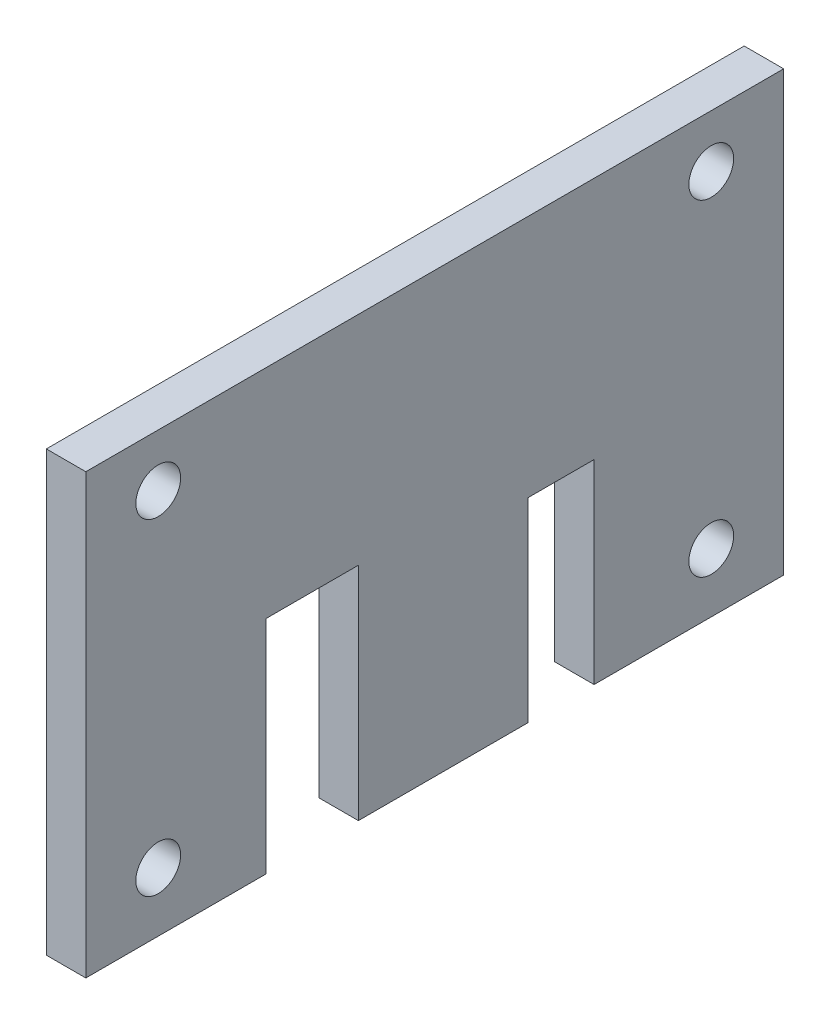
SolidWorks part; units mm, degrees
ref_plane "Front Plane" through (0, 0, 0) normal (0, 0, 1) x (1, 0, 0)
ref_plane "Top Plane" through (0, 0, 0) normal (0, 1, 0) x (1, 0, 0)
ref_plane "Right Plane" through (0, 0, 0) normal (1, 0, 0) x (0, 0, -1)
ref_plane "PX72_4" through (72.4, 0, 0) normal (1, 0, 0) x (0, 0, -1)
sketch "Sketch1" plane through (72.4, 0, 0) normal (1, 0, 0) x (0, 0, -1)
  line L0 (-99.5, -26.8) -> (-46.5, -26.8)
  line L1 (-46.5, -26.8) -> (-46.5, 6.5)
  line L2 (-46.5, 6.5) -> (-99.5, 6.5)
  line L3 (-99.5, 6.5) -> (-99.5, -26.8)
extrude "Cover Plate" add sketch "Sketch1" along normal blind 3
ref_plane "PX71_4" through (71.4, 0, 0) normal (1, 0, 0) x (0, 0, -1)
sketch "Sketch2" plane through (71.4, 0, 0) normal (1, 0, 0) x (0, 0, -1)
  line L0 (-85.8, -27.8) -> (-78.8, -27.8)
  line L1 (-78.8, -27.8) -> (-78.8, -10)
  line L2 (-78.8, -10) -> (-85.8, -10)
  line L3 (-85.8, -10) -> (-85.8, -27.8)
  line L4 (-65.9, -27.8) -> (-60.9, -27.8)
  line L5 (-60.9, -27.8) -> (-60.9, -12)
  line L6 (-60.9, -12) -> (-65.9, -12)
  line L7 (-65.9, -12) -> (-65.9, -27.8)
extrude "Cable Notches" cut sketch "Sketch2" along normal blind 5
sketch "Sketch3" plane through (71.4, 0, 0) normal (1, 0, 0) x (0, 0, -1)
  circle A0 centre (-94, -22.3) radius 1.7
  circle A1 centre (-94, 2.5) radius 1.7
  circle A2 centre (-52, -22.3) radius 1.7
  circle A3 centre (-52, 2.5) radius 1.7
extrude "Screw Holes" cut sketch "Sketch3" along normal blind 5
equation "\"BOARD_REAR\" = 86.0"
equation "\"BOARD_FRONT\" = 41.0"
equation "\"BOARD_END\" = 22.0"
equation "\"BOARD_ANGLED\" = 30.0"
equation "\"BOARD_DEPTH\" = 41.8431"
equation "\"PCB_T\" = 1.6"
equation "\"ABOVE_PCB\" = 14.0"
equation "\"BELOW_PCB\" = 6.0"
equation "\"MID_PARTS_H\" = 9.0"
equation "\"BOARD_HOLE_PILOT\" = 1.6"
equation "\"J2_X\" = 19.0"
equation "\"DUPONT_DROP\" = 14.0"
equation "\"BEND_R\" = 5.0"
equation "\"BOARD_GAP\" = 3.0"
equation "\"TOF_FOV\" = 25.0"
equation "\"TOF_MARGIN_DEG\" = 5.0"
equation "\"TOF_WIN_MARGIN\" = 1.0"
equation "\"TOF_Z\" = 9.0"
equation "\"TOF_SIDE_BEARING\" = 90.0"
equation "\"TOF_CONE_LEN\" = 70.0"
equation "\"CAM_W\" = 29.2"
equation "\"CAM_H\" = 28.2"
equation "\"CAM_D\" = 12.35"
equation "\"CAM_FRONT_Y\" = 43.0"
equation "\"CAM_BOTTOM_Z\" = 17.0"
equation "\"CAM_LENS_UP\" = 11.6"
equation "\"CAM_LENS_OPEN\" = 9.6"
equation "\"CAM_HFOV\" = 53.5"
equation "\"CAM_VFOV\" = 41.41"
equation "\"CAM_FOV_MARGIN\" = 3.0"
equation "\"CAM_FIT\" = 0.3"
equation "\"RIBBON_W\" = 16.0"
equation "\"RIBBON_T\" = 0.3"
equation "\"RIBBON_LEN\" = 150.0"
equation "\"RIBBON_EXIT_Y\" = 35.0"
equation "\"WALL\" = 2.4"
equation "\"HEAD_X\" = 48.4"
equation "\"HEAD_REAR_Y\" = -11.9"
equation "\"CAM_FOAM\" = 2.8"
equation "\"HEAD_FRONT_Y\" = 48.2"
equation "\"HEAD_TOP_Z\" = 50.6"
equation "\"HEAD_BOT_Z\" = -28.4"
equation "\"HEAD_SPLIT_Z\" = -4.0"
equation "\"SKIRT_T\" = 1.2"
equation "\"SKIRT_H\" = 3.0"
equation "\"SKIRT_FIT\" = 0.3"
equation "\"VISOR\" = 7.8"
equation "\"VISOR_Z\" = 40.0"
equation "\"ROOF_SLOPE_Y\" = 40.0"
equation "\"ROOF_CHAMFER\" = 10.0"
equation "\"REAR_CHAMFER\" = 10.0"
equation "\"CORNER_CHAMFER\" = 6.0"
equation "\"LOWER_SIDE_FACET\" = 6.0"
equation "\"LIGHTBAR_DEPTH\" = 1.0"
equation "\"HOOD_Z\" = 14.0"
equation "\"HOOD_L\" = 6.0"
equation "\"SIDE_HOOD_L\" = 4.0"
equation "\"INSERT_M3_D\" = 4.0"
equation "\"INSERT_M3_L\" = 6.0"
equation "\"M3_CLEAR\" = 3.4"
equation "\"M2_PILOT\" = 1.6"
equation "\"M25_PILOT\" = 2.2"
equation "\"BOX_X\" = 72.4"
equation "\"BOX_FRONT_Y\" = -11.9"
equation "\"BOX_REAR_Y\" = -124.4"
equation "\"BOX_BOT_Z\" = -28.4"
equation "\"BOX_TOP_Z\" = 26.0"
equation "\"LID_T\" = 2.4"
equation "\"LID_SKIRT\" = 1.6"
equation "\"LID_TONGUE_H\" = 3.0"
equation "\"LID_FIT\" = 0.3"
equation "\"PI_STANDOFF\" = 8.0"
equation "\"BOX_REAR_CHAMFER\" = 8.0"
equation "\"BOX_REAR_FACET\" = 4.0"
equation "\"VENT_UPSTAND\" = 3.0"
equation "\"TUBE_D\" = 22.2"
equation "\"TUBE_LINER\" = 1.0"
equation "\"MOUNT_Y\" = -70.0"
equation "\"RAIL_W\" = 30.0"
equation "\"RAIL_W2\" = 38.0"
equation "\"RAIL_H\" = 6.0"
equation "\"SLIDE\" = 0.3"
equation "\"STOP_T\" = 6.0"
equation "\"CLAMP_W\" = 40.0"
equation "\"CLAMP_HALF\" = 20.0"
equation "\"CLAMP_DROP\" = 12.0"
equation "\"CAP_T\" = 12.0"
equation "\"CLAMP_BOLT_OFF\" = 16.6"
equation "\"M5_INSERT_D\" = 6.4"
equation "\"M5_CLEAR\" = 5.5"
equation "\"LOCK_D\" = 3.3"
equation "\"POD_TILT_DEG\" = 0.0"
equation "\"PRINT_LIMIT\" = 180.0"
equation "\"PI5_L\" = 85.0"
equation "\"PI5_W\" = 56.0"
equation "\"PI5_T\" = 1.6"
equation "\"PI5_USBC_BX\" = 11.2"
equation "\"PI5_ETH_BY\" = 10.2"
equation "\"PI5_PORT_OVERHANG\" = 3.0"
equation "\"PI5_FPC_H\" = 5.0"
equation "\"PI5_FPC_USE\" = 0.0"
equation "\"PI5_PIN1_BX\" = 8.37"
equation "\"HEADER_BASE_H\" = 2.5"
equation "\"DUPONT_L\" = 14.0"
equation "\"PI5_UNDERSIDE\" = 1.5"
equation "\"COOLER_H\" = 15.0"
equation "\"HAT_W\" = 65.0"
equation "\"HAT_D\" = 56.5"
equation "\"HAT_T\" = 1.6"
equation "\"HAT_SPACER\" = 16.0"
equation "\"HAILO_H\" = 10.0"
equation "\"STACK_PINS_H\" = 6.0"
equation "\"DUPONT_SEAT\" = 0.5"
equation "\"PCIE_FFC_LOOP\" = 6.0"
equation "\"HAILO_AIR_GAP_MIN\" = 8.0"
equation "\"M25_CLEAR\" = 2.7"
equation "\"PI_X0\" = -55.0"
equation "\"PI_Y1\" = -36.5"
equation "\"PI_Y0\" = -92.5"
equation "\"BOX_LEN\" = 112.5"
equation "\"COVER_T\" = 3.0"
equation "\"COVER_TOP_Z\" = 6.5"
equation "\"SIDE_LEDGE_Z\" = -2.5"
equation "\"UPPER_LEDGE_Z\" = 15.5"
equation "\"REAR_LEDGE_Z\" = 8.0"
equation "\"LEDGE_L\" = 4.0"
equation "\"RIBBON_W_PI\" = 11.5"
equation "\"RIBBON_RUN_Z\" = 12.0"
equation "\"RIBBON_SPEC_LEN\" = 200.0"
